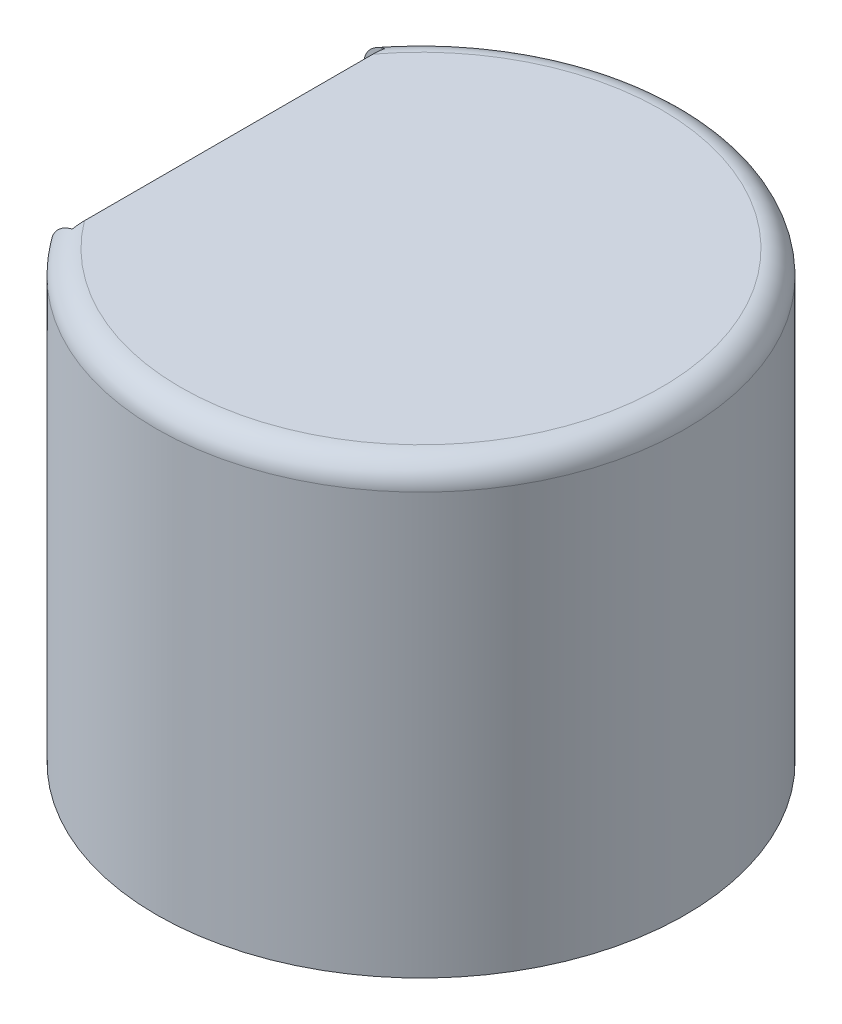
SolidWorks part; units mm, degrees
ref_plane "Front Plane" through (0, 0, 0) normal (0, 0, 1) x (1, 0, 0)
ref_plane "Top Plane" through (0, 0, 0) normal (0, 1, 0) x (1, 0, 0)
ref_plane "Right Plane" through (0, 0, 0) normal (1, 0, 0) x (0, 0, -1)
sketch "Sketch1" plane through (0, 0, 0) normal (0, 1, 0) x (1, 0, 0)
  circle A0 centre (0, 0) radius 11
extrude "Boss-Extrude1" add sketch "Sketch1" against normal blind 18.5
sketch "Sketch4" plane through (0, 0, 0) normal (0, 1, 0) x (1, 0, 0)
  line L0 (11, 0) -> (-8, 0)
  line L1 (-8, 0) -> (-8, -6.5)
  line L2 (-8, 0) -> (-8, 6.5)
  line L3 (-8, -6.5) -> (-8.8741, -6.5)
  line L4 (-8, 6.5) -> (-8.8741, 6.5)
  circle A0 centre (0, 0) radius 11
  circle M1 centre (0, 0) radius 11
  dimension "D2" = 22
  dimension "D1" = 19
  dimension "D3" = 6.5
  dimension "D4" = 6.5
extrude "Cut-Extrude1" cut sketch "Sketch4" against normal blind 4 contours L2 L4 L3 L1 M1
fillet "Fillet1" radius 1 1 edges at (11, 0, 0)
